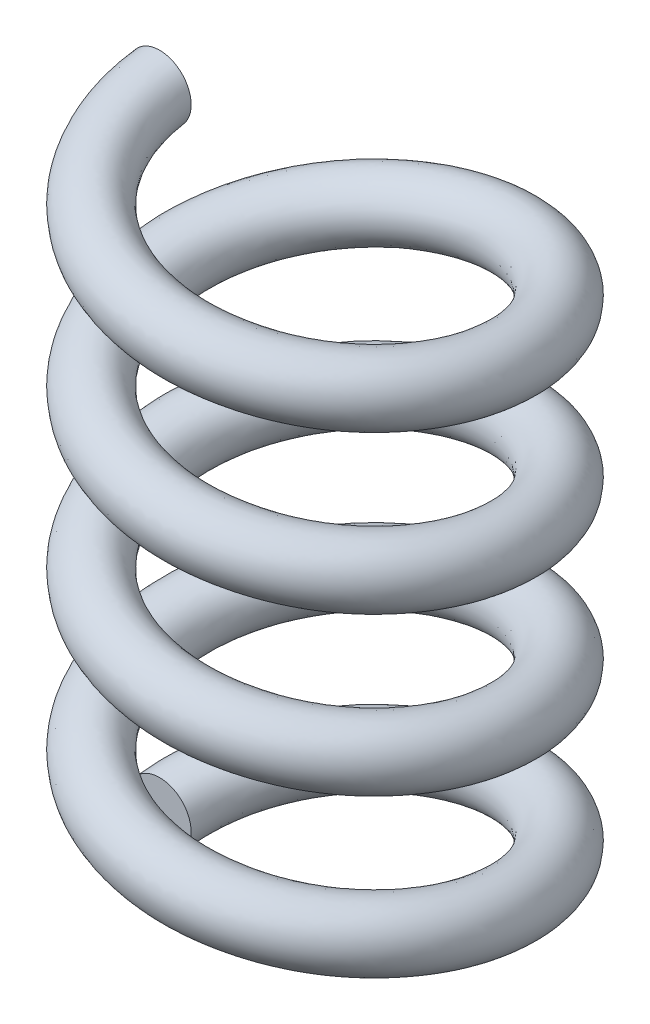
SolidWorks part; units mm, degrees
material "合金钢"
ref_plane "前视基准面" through (0, 0, 0) normal (0, 0, 1) x (1, 0, 0)
ref_plane "上视基准面" through (0, 0, 0) normal (0, 1, 0) x (1, 0, 0)
ref_plane "右视基准面" through (0, 0, 0) normal (1, 0, 0) x (0, 0, -1)
sketch "草图1" plane through (0, 0, 0) normal (0, 1, 0) x (1, 0, 0)
  circle A0 centre (0, 0) radius 2.75
  dimension "D1" = 5.5
curve "螺旋线/涡状线1" pitch 2 height 8 turns 4
sketch "草图2" plane through (0, 0, 0) normal (0, 0, 1) x (1, 0, 0)
  circle A0 centre (-2.1, 7.3643) radius 0.4
  dimension "D1" = 0.8
  dimension "D2" = 2.1
sweep "扫描1" add profiles "草图2" path "螺旋线/涡状线1"
sketch "草图3" plane through (0, 0, 0) normal (0, 1, 0) x (1, 0, 0)
  circle A0 centre (0, 0) radius 2.5
  dimension "D1" = 5
